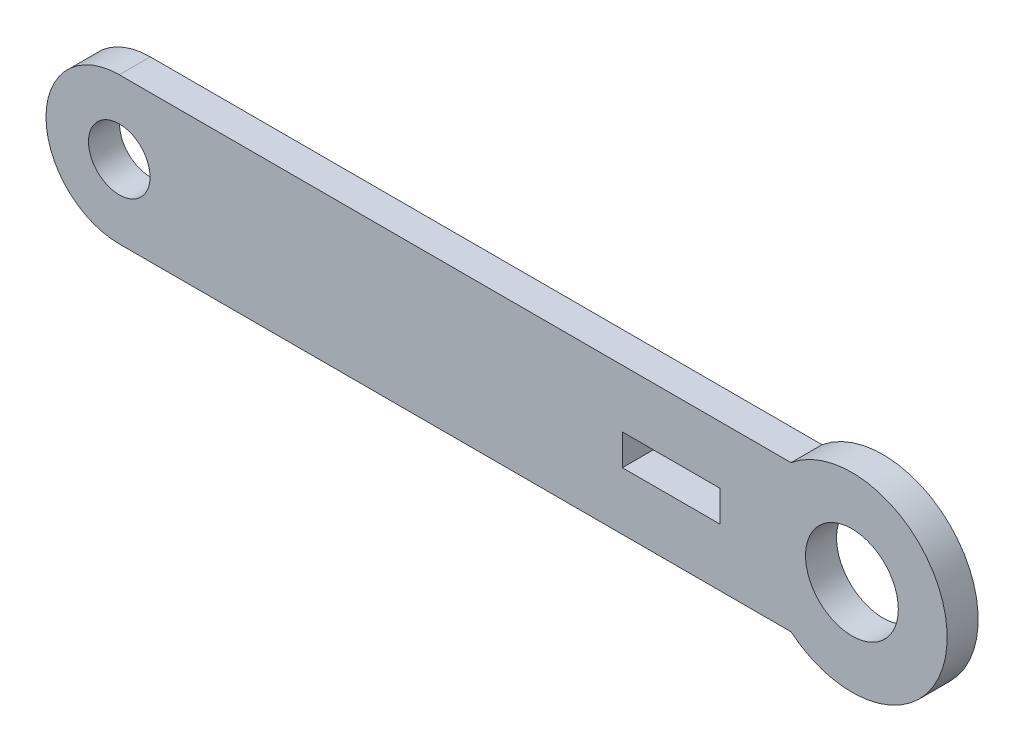
SolidWorks part; units mm, degrees
ref_plane "Front Plane" through (0, 0, 0) normal (0, 0, 1) x (1, 0, 0)
ref_plane "Top Plane" through (0, 0, 0) normal (0, 1, 0) x (1, 0, 0)
ref_plane "Right Plane" through (0, 0, 0) normal (1, 0, 0) x (0, 0, -1)
sketch "Sketch1" plane through (0, 0, 0) normal (0, 0, 1) x (1, 0, 0)
  line L0 (-37.5, 0) -> (37.5, 0)
  line L1 (-37.5, 0) -> (37.5, 0) construction
  line L2 (-37.5, 7.5) -> (37.5, 7.5)
  line L3 (-37.5, -7.5) -> (37.5, -7.5)
  arc A0 (-37.5, 7.5) -> (-37.5, -7.5) centre (-37.5, 0) ccw
  arc A1 (37.5, -7.5) -> (37.5, 7.5) centre (37.5, 0) ccw
  circle A2 centre (-37.5, 0) radius 3.15
  circle A3 centre (37.5, 0) radius 4.75
  circle A4 centre (37.5, 0) radius 9.75
  point P0 (0, 0)
  point P4 (0, 0)
  dimension "D1" = 6.3
  dimension "D2" = 9.5
  dimension "D3" = 7.5
  dimension "D4" = 75
  dimension "D5" = 5
extrude "Boss-Extrude1" add sketch "Sketch1" along normal blind 3.175
sketch "Sketch2" plane through (0, 0, 3.175) normal (0, 0, 1) x (1, 0, 0)
  line L1 (-25, -1.5875) -> (-10, -1.5875)
  line L2 (-25, -1.5875) -> (-25, 1.5875)
  line L3 (-25, 1.5875) -> (-10, 1.5875)
  line L4 (-10, -1.5875) -> (-10, 1.5875)
  line L5 (-25, -1.5875) -> (-10, 1.5875) construction
  line L6 (-25, 1.5875) -> (-10, -1.5875) construction
  line L7 (14, -1.5875) -> (24, -1.5875)
  line L8 (14, -1.5875) -> (14, 1.5875)
  line L9 (14, 1.5875) -> (24, 1.5875)
  line L10 (24, -1.5875) -> (24, 1.5875)
  line L11 (14, -1.5875) -> (24, 1.5875) construction
  line L12 (14, 1.5875) -> (24, -1.5875) construction
  point P0 (-17.5, 0)
  point P5 (19, 0)
  dimension "D1" = 3.175
  dimension "D2" = 3.175
  dimension "D3" = 10
  dimension "D4" = 15
  dimension "D5" = 14
  dimension "D6" = 10
  dimension "D7" = 1.5875
  dimension "D8" = 0
extrude "Cut-Extrude1" cut sketch "Sketch2" against normal through all contours L2 L1 L4 L3 | L8 L7 L10 L9
sketch "Sketch4" plane through (0, 0, 3.175) normal (0, 0, 1) x (1, 0, 0)
  line L1 (-27.4614, -3.6305) -> (-7.4472, -3.6305)
  line L2 (-27.4614, -3.6305) -> (-27.4614, 3.6305)
  line L3 (-27.4614, 3.6305) -> (-7.4472, 3.6305)
  line L4 (-7.4472, -3.6305) -> (-7.4472, 3.6305)
extrude "Boss-Extrude2" add sketch "Sketch4" against normal up to surface (3.175 mm away) up to face at (19, 0, 0)
